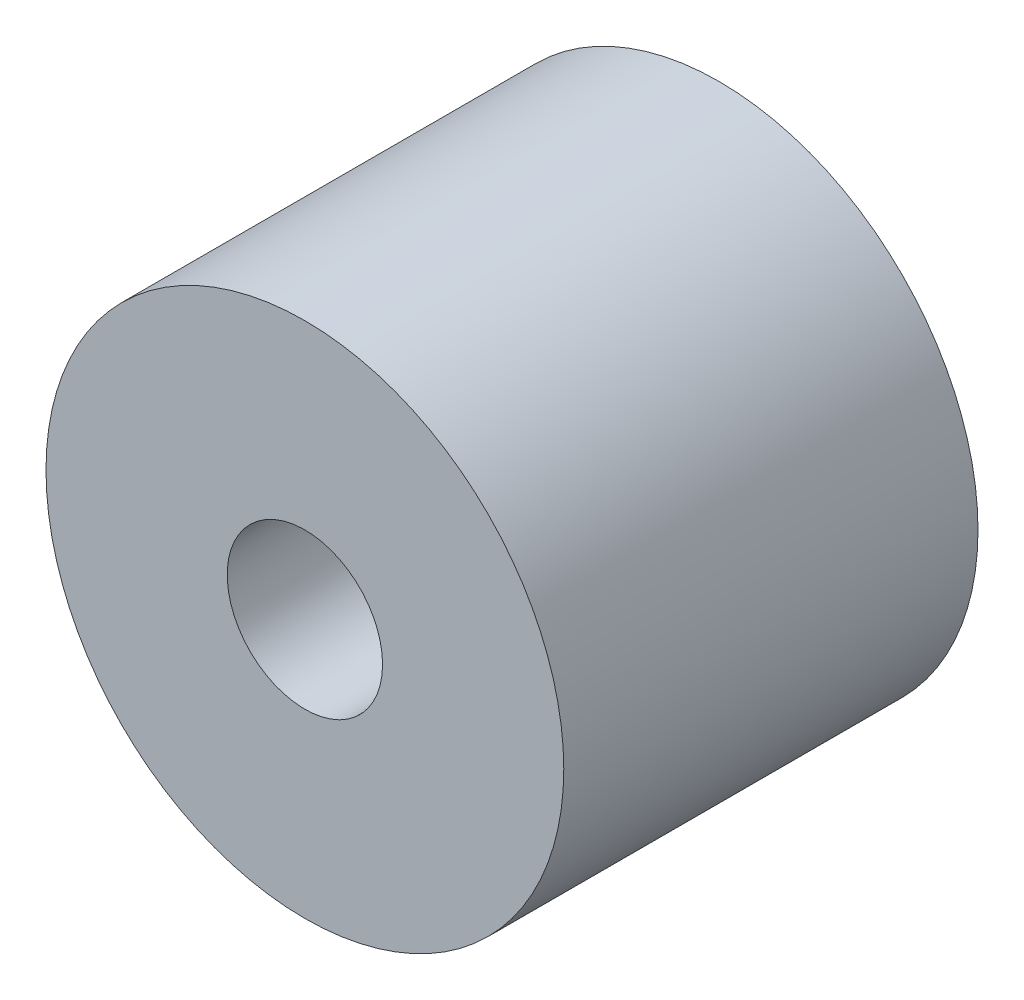
SolidWorks part; units mm, degrees
ref_plane "Front Plane" through (0, 0, 0) normal (0, 0, 1) x (1, 0, 0)
ref_plane "Top Plane" through (0, 0, 0) normal (0, 1, 0) x (1, 0, 0)
ref_plane "Right Plane" through (0, 0, 0) normal (1, 0, 0) x (0, 0, -1)
sketch "Sketch1" plane through (0, 0, 0) normal (0, 0, 1) x (1, 0, 0)
  circle A0 centre (-51.3929, 26.0662) radius 5
  circle A1 centre (-51.3929, 26.0662) radius 1.5
extrude "Boss-Extrude1" add sketch "Sketch1" along normal blind 8
